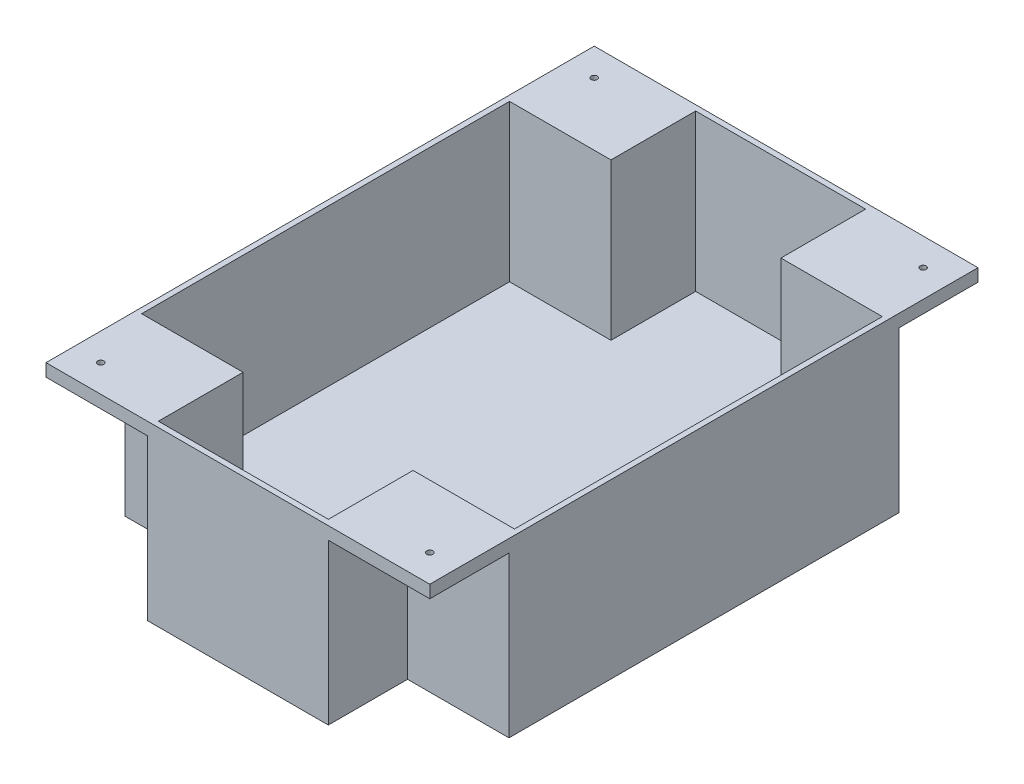
SolidWorks part; units mm, degrees
ref_plane "Alzado" through (0, 0, 0) normal (0, 0, 1) x (1, 0, 0)
ref_plane "Planta" through (0, 0, 0) normal (0, 1, 0) x (1, 0, 0)
ref_plane "Vista lateral" through (0, 0, 0) normal (1, 0, 0) x (0, 0, -1)
sketch "Croquis1" plane through (0, 0, 0) normal (0, 1, 0) x (1, 0, 0)
  line L1 (-35, -50) -> (35, -50)
  line L2 (-35, -50) -> (-35, 50)
  line L3 (-35, 50) -> (35, 50)
  line L4 (35, -50) -> (35, 50)
  line L5 (-35, -50) -> (35, 50) construction
  line L6 (-35, 50) -> (35, -50) construction
  point P0 (0, 0)
  dimension "D1" = 70
  dimension "D2" = 100
extrude "Saliente-Extruir1" add sketch "Croquis1" along normal blind 3
sketch "Croquis2" plane through (0, 3, 0) normal (0, 1, 0) x (1, 0, 0)
  line L0 (-16.5, -50) -> (-16.5, -34.55)
  line L5 (-35, -50) -> (35, -50) construction
  line L6 (-16.5, -34.55) -> (-35, -34.55)
  line L7 (-35, 50) -> (-35, -50) construction
  line L8 (-35, -34.55) -> (-35, -32.494)
  line L11 (-15.5, -50) -> (-16.5, -50)
  line L12 (-34, -33.55) -> (-34, 0.056)
  line L14 (-35, 0.056) -> (-35, -32.494)
  line L15 (-34, -33.55) -> (-15.5, -33.55)
  line L16 (0, 10.6275) -> (0, -9.2871) construction
  line L17 (-13.6252, 0) -> (15.9449, 0) construction
  line L18 (-15.5, -50) -> (15.5, -50)
  line L20 (15.5, -49) -> (-15.5, -49)
  line L21 (-15.5, -33.55) -> (-15.5, -49)
  line L22 (34, -33.55) -> (15.5, -33.55)
  line L23 (34, -33.55) -> (34, 0.056)
  line L25 (35, 0.056) -> (35, -32.494)
  line L26 (35, -34.55) -> (35, -32.494)
  line L27 (16.5, -34.55) -> (35, -34.55)
  line L28 (16.5, -50) -> (16.5, -34.55)
  line L29 (15.5, -50) -> (16.5, -50)
  line L30 (15.5, -33.55) -> (15.5, -49)
  line L31 (-34, 33.55) -> (-15.5, 33.55)
  line L32 (-34, 33.55) -> (-34, -0.056)
  line L34 (-35, -0.056) -> (-35, 32.494)
  line L35 (-35, 34.55) -> (-35, 32.494)
  line L36 (-16.5, 34.55) -> (-35, 34.55)
  line L37 (-16.5, 50) -> (-16.5, 34.55)
  line L38 (-15.5, 50) -> (-16.5, 50)
  line L39 (-15.5, 50) -> (15.5, 50)
  line L41 (15.5, 49) -> (-15.5, 49)
  line L42 (-15.5, 33.55) -> (-15.5, 49)
  line L43 (34, 33.55) -> (34, -0.056)
  line L45 (35, -0.056) -> (35, 32.494)
  line L46 (35, 34.55) -> (35, 32.494)
  line L47 (16.5, 34.55) -> (35, 34.55)
  line L48 (16.5, 50) -> (16.5, 34.55)
  line L49 (15.5, 50) -> (16.5, 50)
  line L50 (-15.5, 50) -> (15.5, 50)
  line L51 (-15.5, 50) -> (-16.5, 50)
  line L52 (-16.5, 50) -> (-16.5, 34.55)
  line L53 (-16.5, 34.55) -> (-35, 34.55)
  line L54 (-35, 34.55) -> (-35, 32.494)
  line L55 (-35, -0.056) -> (-35, 32.494)
  line L57 (-34, 33.55) -> (-34, -0.056)
  line L58 (-34, 33.55) -> (-15.5, 33.55)
  line L59 (-15.5, 33.55) -> (-15.5, 49)
  line L60 (15.5, 49) -> (-15.5, 49)
  line L61 (15.5, 33.55) -> (15.5, 49)
  line L62 (34, 33.55) -> (15.5, 33.55)
  dimension "D1" = 1
  dimension "D2" = 1
  dimension "D3" = 1
  dimension "D4" = 15.45
  dimension "D5" = 18.5
  dimension "D6" = 1
  dimension "D7" = 1
extrude "Saliente-Extruir2" add sketch "Croquis2" along normal blind 28.5
sketch "Croquis3" plane through (0, 0, 0) normal (0, -1, 0) x (1, 0, 0)
  line L0 (0, -3.8109) -> (0, 10.0038) construction
  line L5 (-6.1192, 0) -> (6.5841, 0) construction
  circle A0 centre (-30, -45) radius 0.56
  circle A1 centre (-30, 45) radius 0.56
  circle A2 centre (30, -45) radius 0.56
  circle A3 centre (30, 45) radius 0.56
  dimension "D3" = 1.12
extrude "Cortar-Extruir1" cut sketch "Croquis3" against normal through all
sketch "Croquis4" plane through (0, 0, 0) normal (0, -1, 0) x (1, 0, 0)
  line L2 (0, -2.9757) -> (0, 6.3357) construction
  line L3 (-35, 50) -> (-16.5, 50)
  line L4 (-35, 50) -> (-35, 35.55)
  line L5 (-35, 35.55) -> (-16.5, 35.55)
  line L6 (-16.5, 50) -> (-16.5, 35.55)
  line L7 (2.5805, 0) -> (-3.1681, 0) construction
  line L8 (35, 35.55) -> (16.5, 35.55)
  line L9 (16.5, 50) -> (16.5, 35.55)
  line L10 (35, 50) -> (16.5, 50)
  line L11 (35, 50) -> (35, 35.55)
  line L12 (35, -50) -> (35, -35.55)
  line L13 (35, -50) -> (16.5, -50)
  line L14 (16.5, -50) -> (16.5, -35.55)
  line L15 (35, -35.55) -> (16.5, -35.55)
  line L16 (-35, -35.55) -> (-16.5, -35.55)
  line L17 (-16.5, -50) -> (-16.5, -35.55)
  line L18 (-35, -50) -> (-16.5, -50)
  line L19 (-35, -50) -> (-35, -35.55)
  dimension "D1" = 18.5
  dimension "D2" = 14.45
extrude "Cortar-Extruir2" cut sketch "Croquis4" against normal blind 29.2
